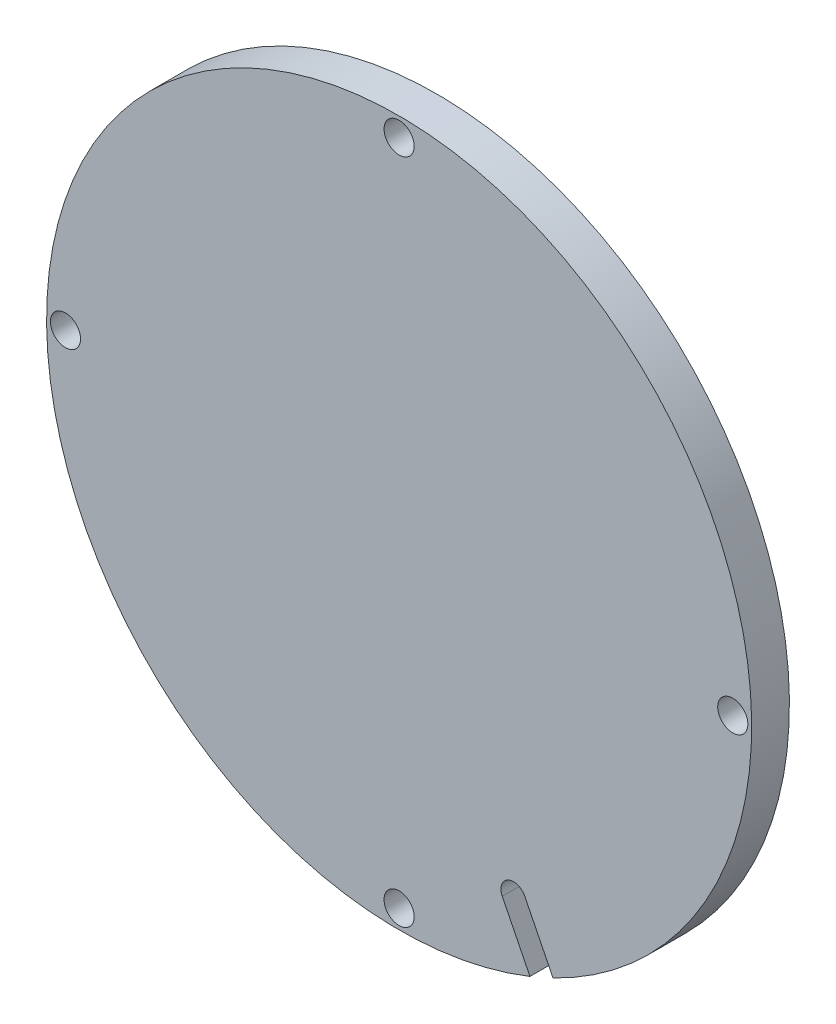
SolidWorks part; units mm, degrees
ref_plane "Front Plane" through (0, 0, 0) normal (0, 0, 1) x (1, 0, 0)
ref_plane "Top Plane" through (0, 0, 0) normal (0, 1, 0) x (1, 0, 0)
ref_plane "Right Plane" through (0, 0, 0) normal (1, 0, 0) x (0, 0, -1)
sketch "Sketch2" plane through (0, 0, 0) normal (0, 0, 1) x (1, 0, 0)
  circle A0 centre (0, 0) radius 44.45
  dimension "D1" = 88.9
extrude "Boss-Extrude1" add sketch "Sketch2" along normal blind 4.7625 contours A0
hole_wizard "#6 Clearance Hole1" positions "Sketch3" profile "Sketch4" hole size "#6" standard "ANSI Inch" end condition up to next
sketch "Sketch3" plane through (0, 0, 4.7625) normal (0, 0, 1) x (1, 0, 0)
  circle A0 centre (0, 0) radius 44.45 construction
  point P0 (0, 42.0688)
  dimension "D1" = 42.0688
sketch "Sketch4" plane through (0, 42.0688, 4.7625) normal (1, 0, 0) x (0, -1, 0)
  line L0 (0, 0) -> (0, 4.7635)
  line L1 (0, 4.7635) -> (1.8986, 4.7635)
  line L2 (1.8986, 4.7635) -> (1.8986, 0)
  line L5 (1.8986, 0) -> (0, 0)
  line L11 (0, -6.35) -> (0, 107.95) construction
  dimension "Thru Hole Dia." = 3.7973
  dimension "Thru Hole Depth" = 4.7635
pattern_circular "CirPattern1" count 4 over 360 about axis through (0, 0, 0) along (0, 0, 1) of "#6 Clearance Hole1"
sketch "Sketch5" plane through (0, 0, 4.7625) normal (0, 0, 1) x (1, 0, 0)
  line L0 (17.9605, -40.6598) -> (14.423, -33.5542) construction
  line L1 (16.5394, -41.3673) -> (13.0019, -34.2617)
  line L2 (19.3816, -39.9523) -> (15.8441, -32.8467)
  circle A0 centre (0, 0) radius 44.45 construction
  arc A1 (16.5394, -41.3673) -> (19.3816, -39.9523) centre (17.9605, -40.6598) ccw
  arc A2 (15.8441, -32.8467) -> (13.0019, -34.2617) centre (14.423, -33.5542) ccw
  point P4 (16.1917, -37.107)
  dimension "D1" = 3.175
  dimension "D2" = 7.9375
extrude "Cut-Extrude1" cut sketch "Sketch5" against normal through all both and the other way through all contours L2 A2 L1 A1
